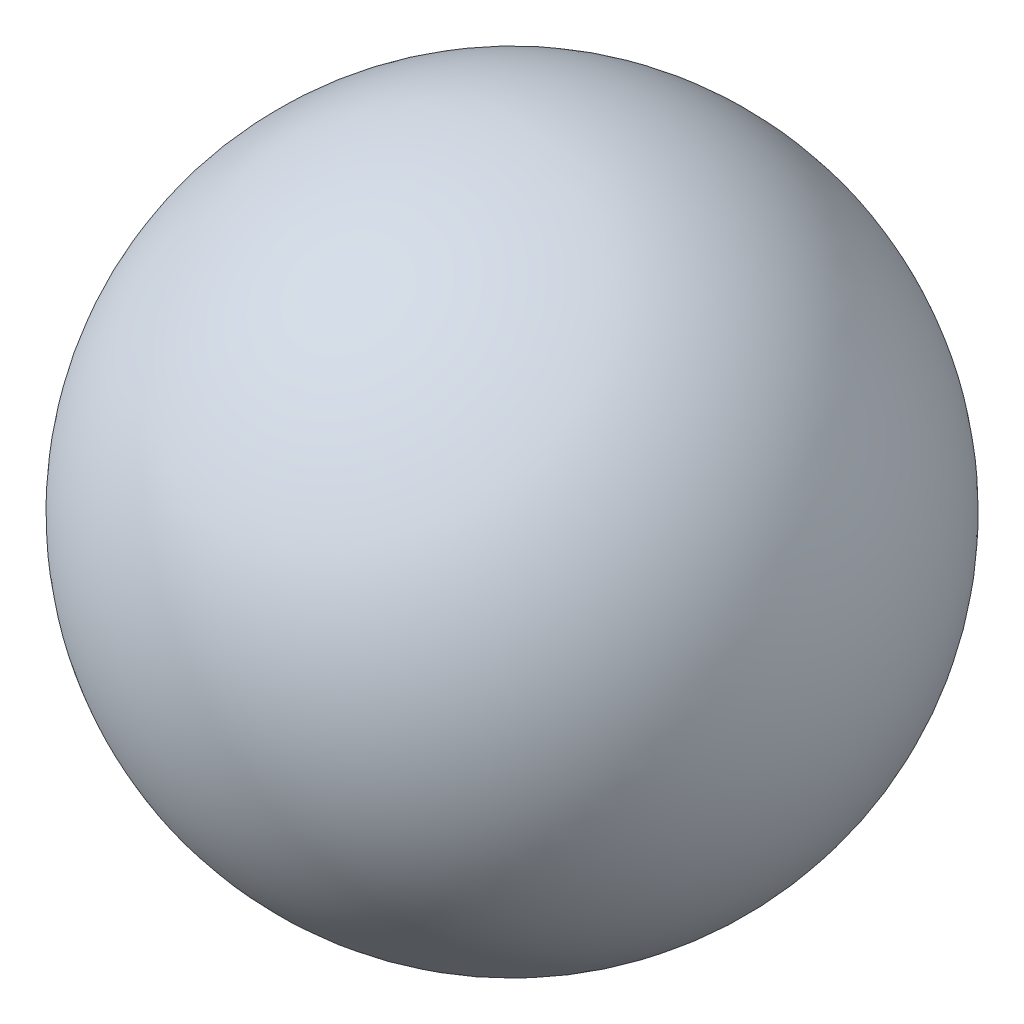
SolidWorks part; units mm, degrees
ref_plane "Front" through (0, 0, 0) normal (0, 0, 1) x (1, 0, 0)
ref_plane "Top" through (0, 0, 0) normal (0, 1, 0) x (1, 0, 0)
ref_plane "Right" through (0, 0, 0) normal (1, 0, 0) x (0, 0, -1)
sketch "Sketch1" plane through (0, 0, 0) normal (0, 1, 0) x (1, 0, 0)
  line L0 (0, 21.335) -> (0, 0)
  line L1 (0, 0) -> (0, -21.335)
  line L2 (0, 26.6915) -> (0, 40.2941)
  arc A0 (0, -21.335) -> (0, 21.335) centre (0, 0) ccw
  dimension "D1" = 42.67
revolve "Revolve2" add sketch "Sketch1" angle 360 about L2
